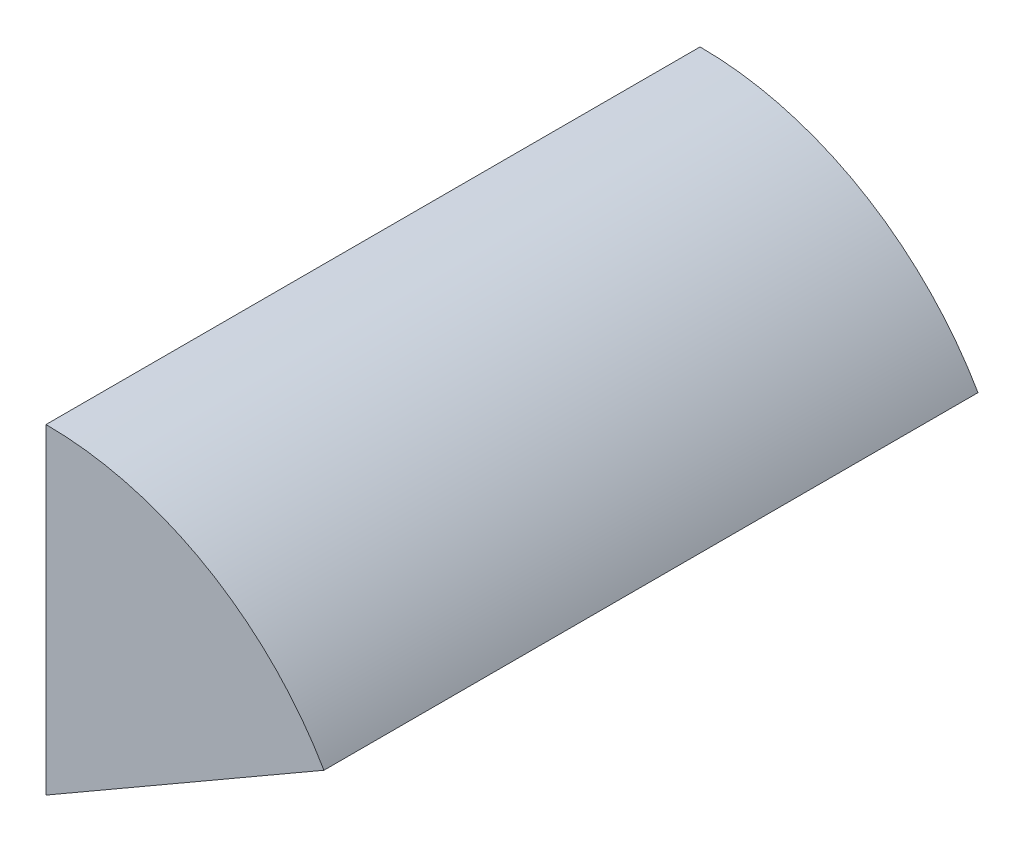
SolidWorks part; units mm, degrees
ref_plane "Alzado" through (0, 0, 0) normal (0, 0, 1) x (1, 0, 0)
ref_plane "Planta" through (0, 0, 0) normal (0, 1, 0) x (1, 0, 0)
ref_plane "Vista lateral" through (0, 0, 0) normal (1, 0, 0) x (0, 0, -1)
sketch "Croquis1" plane through (0, 0, 0) normal (0, 0, 1) x (1, 0, 0)
  line L0 (0, 24.5325) -> (0, 0)
  line L1 (0, 0) -> (21.2458, 12.2663)
  arc A1 (21.2458, 12.2663) -> (0, 24.5325) centre (0, 0) ccw
  dimension "D1" = 60
extrude "Saliente-Extruir1" add sketch "Croquis1" along normal blind 50
sketch "Croquis2" plane through (0, 0, 0) normal (0, 0, -1) x (-1, 0, 0)
  circle A0 centre (-7.5627, 13.2928) radius 5
  dimension "D1" = 10
extrude "Cortar-Extruir1" cut sketch "Croquis2" against normal blind 10
